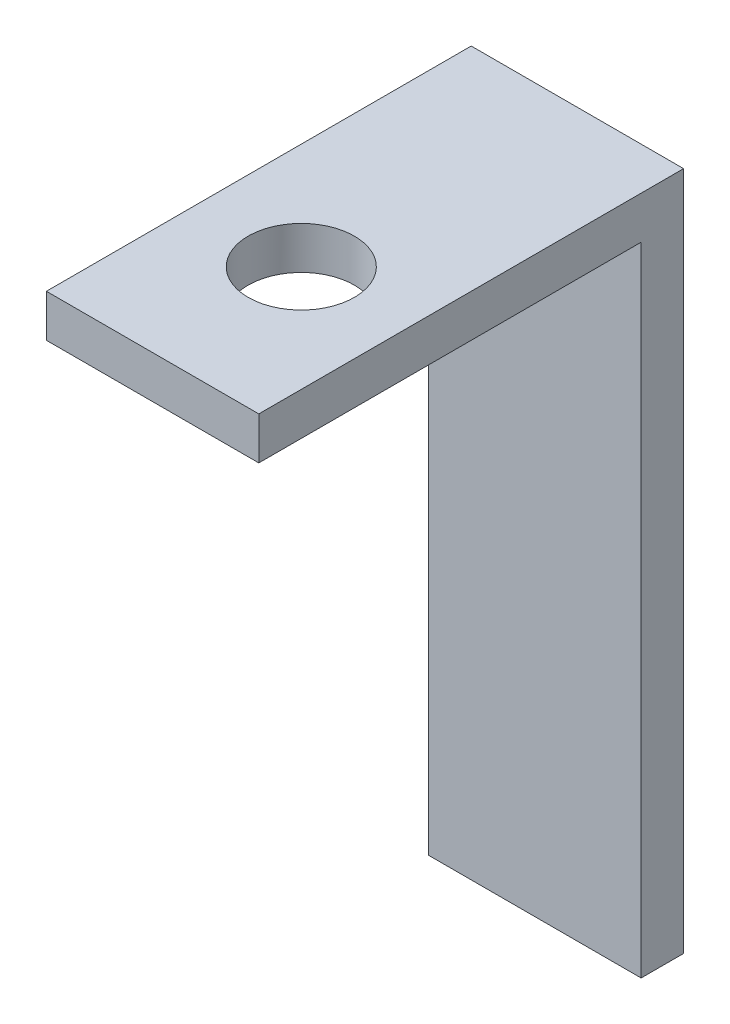
SolidWorks part; units mm, degrees
ref_plane "Front Plane" through (0, 0, 0) normal (0, 0, 1) x (1, 0, 0)
ref_plane "Top Plane" through (0, 0, 0) normal (0, 1, 0) x (1, 0, 0)
ref_plane "Right Plane" through (0, 0, 0) normal (1, 0, 0) x (0, 0, -1)
sketch "Sketch1" plane through (0, 0, 0) normal (0, 0, 1) x (1, 0, 0)
  line L1 (-5, 16) -> (5, 16)
  line L2 (-5, 16) -> (-5, -16)
  line L3 (-5, -16) -> (5, -16)
  line L4 (5, 16) -> (5, -16)
  line L5 (-5, 16) -> (5, -16) construction
  line L6 (-5, -16) -> (5, 16) construction
  point P0 (0, 0)
  dimension "D1" = 10
  dimension "D2" = 32
extrude "Boss-Extrude1" add sketch "Sketch1" along normal blind 2
sketch "Sketch2" plane through (0, 0, 2) normal (0, 0, 1) x (1, 0, 0)
  line L0 (5, -16) -> (5, 16) construction
  line L1 (-5, 16) -> (5, 16)
  line L2 (-5, 16) -> (-5, 14)
  line L3 (-5, 14) -> (5, 14)
  line L4 (5, 16) -> (5, 14)
  line L5 (-5, 16) -> (5, 14) construction
  line L6 (-5, 14) -> (5, 16) construction
  line L7 (5, 16) -> (-5, 16) construction
  point P0 (0, 15)
  dimension "D1" = 2
extrude "Boss-Extrude2" add sketch "Sketch2" along normal blind 18
sketch "Sketch3" plane through (0, 16, 0) normal (0, 1, 0) x (1, 0, 0)
  line L0 (5, 0) -> (-5, 0) construction
  circle A0 centre (0, -13) radius 2.5
  dimension "D1" = 5
  dimension "D2" = 13
extrude "Cut-Extrude1" cut sketch "Sketch3" against normal up to surface (2 mm away) up to face at (-1.25, 14, 15.5)
